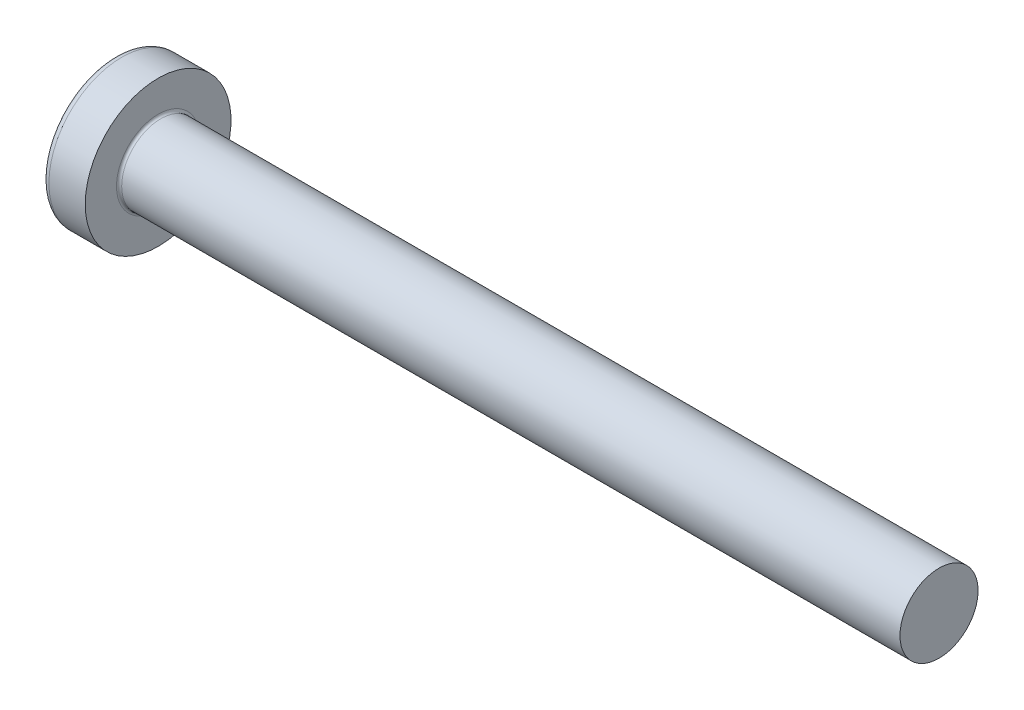
SolidWorks part; units mm, degrees
ref_plane "Plane1" through (0, 0, 0) normal (0, 0, 1) x (1, 0, 0)
ref_plane "Plane2" through (0, 0, 0) normal (0, 1, 0) x (1, 0, 0)
ref_plane "Plane3" through (0, 0, 0) normal (1, 0, 0) x (0, 0, -1)
sketch "BodySke" plane through (0, 0, 0) normal (0, 0, 1) x (1, 0, 0)
  line L0 (2.4, 1.5) -> (2.4, 2.8)
  line L1 (2.65, 6.35) -> (2.65, -3.175) construction
  line L2 (-25.4, 0) -> (127, 0) construction
  line L3 (32.4, 0) -> (0, 0)
  line L4 (2.4, 1.5) -> (32.4, 1.5)
  line L5 (32.4, 1.5) -> (32.4, 0)
  line L6 (1.0035, 2.8) -> (2.4, 2.8)
  line L8 (2.4, 6.35) -> (2.4, -3.175) construction
  arc A0 (0.7754, 2.6744) -> (0, 0) centre (5, 0) ccw
  arc A2 (0.7754, 2.6744) -> (1.0035, 2.8) centre (1.0035, 2.53) cw
  dimension "Head_crown_rad" = 5
  dimension "Head_fillet_rad" = 0.27
  dimension "Length" = 30
  dimension "Head_ht" = 2.4
  dimension "Head_dia" = 5.6
  dimension "Advance" = 0.5
  dimension "Thread_nom" = 30
  dimension "Diameter" = 3
revolve "Base-Revolve" add sketch "BodySke"
cosmetic thread "ThreadCosmetic"
fillet "Fillet1" radius 0.1 1 edges at (2.4, 0, 1.5)
sketch "Sketch3" plane through (0, 0, 0) normal (1, 0, 0) x (0, 0, -1)
  line L0 (0.37, -1.4) -> (-0.37, -1.4)
  line L1 (0.37, -1.4) -> (0.37, 1.4)
  line L2 (-0.37, 1.4) -> (0.37, 1.4)
  line L3 (-0.37, 1.4) -> (-0.37, -1.4)
  dimension "Cross_dia" = 2.8
  dimension "D1" = 1.4
  dimension "Cross_width" = 0.74
  dimension "D2" = 0.37
ref_plane "Plane4" through (1.75, 0, 0) normal (1, 0, 0) x (0, 0, -1)
sketch "Sketch4" plane through (1.75, 0, 0) normal (1, 0, 0) x (0, 0, -1)
  line L0 (0.37, -0.5275) -> (-0.37, -0.5275)
  line L1 (0.37, -0.5275) -> (0.37, 0.5275)
  line L2 (-0.37, 0.5275) -> (0.37, 0.5275)
  line L3 (-0.37, 0.5275) -> (-0.37, -0.5275)
  dimension "D1" = 0.74
  dimension "D2" = 1.055
  dimension "D3" = 0.37
  dimension "D4" = 0.5275
loft "Recess" cut profiles "Sketch3", "Sketch4"
pattern_circular "RecPat" count 2 every 90 about axis through (0, 0, 0) along (1, 0, 0) of "Recess"
sketch "RecCorSke" plane through (0, 0, 0) normal (0, 0, 1) x (1, 0, 0)
  line L0 (-3.175, 0) -> (15.875, 0) construction
  line L1 (-25.4, 0) -> (127, 0) construction
  line L2 (0, 0) -> (0, 0.6784)
  line L3 (0, 0.6784) -> (1.75, 0.556)
  line L4 (1.75, 0.556) -> (1.9307, 0)
  line L5 (1.9307, 0) -> (0, 0)
  dimension "Diameter" = 1.112
  dimension "Depth" = 1.75
  dimension "Draft_angle" = 4
  dimension "Bottom_angle" = 18
revolve "RecessCore" cut sketch "RecCorSke" angle 360 about L0
sketch "ThdSchSke" plane through (0, 0, 0) normal (0, 0, 1) x (1, 0, 0)
  line L0 (3.4, -1.2195) -> (3.2036, -1.5)
  line L1 (3.4, -1.2195) -> (3.5964, -1.5)
  line L2 (3.5964, -1.5) -> (3.5964, -1.875)
  line L3 (-3.175, 0) -> (5.1513, 0) construction
  line L5 (3.5964, -1.875) -> (3.2036, -1.875)
  line L6 (3.2036, -1.875) -> (3.2036, -1.5)
  dimension "Diameter" = 3
  dimension "SideAngle" = 55
  dimension "VeeAngle" = 70
  dimension "Thread_minor" = 2.439
  dimension "Overcut" = 3.75
  dimension "Start" = 3.4
revolve "ThreadSchematic" [suppressed] cut sketch "ThdSchSke" angle 360 about L3
pattern_linear "ThdSchPat" [suppressed]
equation "\"D1@Sketch3\" = \"Cross_dia@Sketch3\" / 2"
equation "\"D2@Sketch3\" = \"Cross_width@Sketch3\" / 2"
equation "\"Depth@RecCorSke\" = \"Cross_depth@Plane4\""
equation "\"D1@Sketch4\" = \"Cross_width@Sketch3\""
equation "\"D2@Sketch4\" = \"Cross_dia@Sketch3\" - 2.0 * \"Cross_depth@Plane4\" * tan(26.5  * 0.017453292)"
equation "\"D3@Sketch4\" = \"D1@Sketch4\" / 2"
equation "\"D4@Sketch4\" = \"D2@Sketch4\" / 2"
equation "\"Thread_length@ThreadCosmetic\" = ((sgn( (\"Length@BodySke\" - \"Advance@BodySke\" * 2.0 ) - \"Thread_nom@BodySke\" )-1)*( (\"Length@BodySke\" - \"Advance@BodySke\" * 2.0 ) - \"Thread_nom@BodySke\" ))/-2+ \"Thread_nom@BodySke\""
equation "\"Thread_minor@ThdSchSke\" = \"Thread_minor@ThreadCosmetic\""
equation "\"Diameter@ThdSchSke\" = \"Diameter@BodySke\""
equation "\"Overcut@ThdSchSke\" = \"Diameter@BodySke\" * 1.25"
equation "\"Start@ThdSchSke\" = \"Head_ht@BodySke\" + \"Length@BodySke\" - \"Thread_length@ThreadCosmetic\"  '---Non-countersunk---"
equation "\"Num_threads@ThdSchPat\" = int( \"Thread_length@ThreadCosmetic\" / \"Advance@BodySke\" + 0.999 )  + 1"
equation "\"Advance@ThdSchPat\" = \"Thread_length@ThreadCosmetic\" /  (\"Num_threads@ThdSchPat\" - 1) 'relax it"
